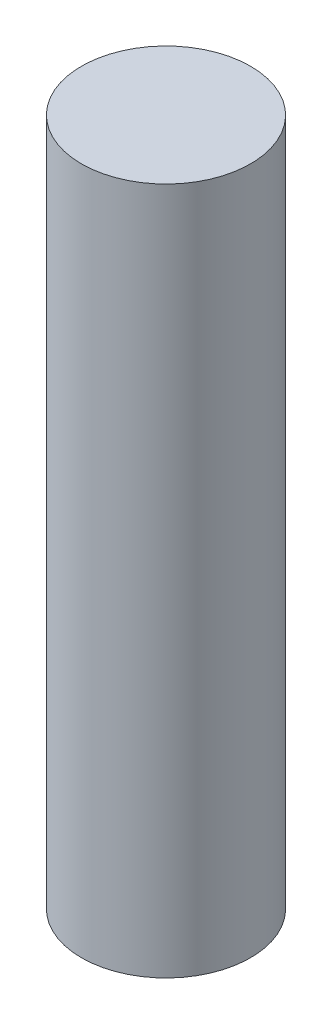
SolidWorks part; units mm, degrees
ref_plane "Front Plane" through (0, 0, 0) normal (0, 0, 1) x (1, 0, 0)
ref_plane "Top Plane" through (0, 0, 0) normal (0, 1, 0) x (1, 0, 0)
ref_plane "Right Plane" through (0, 0, 0) normal (1, 0, 0) x (0, 0, -1)
sketch "Sketch1" plane through (0, 0, 0) normal (0, 1, 0) x (1, 0, 0)
  circle A0 centre (0, 0) radius 12.3
extrude "Boss-Extrude1" add sketch "Sketch1" along normal blind 100
